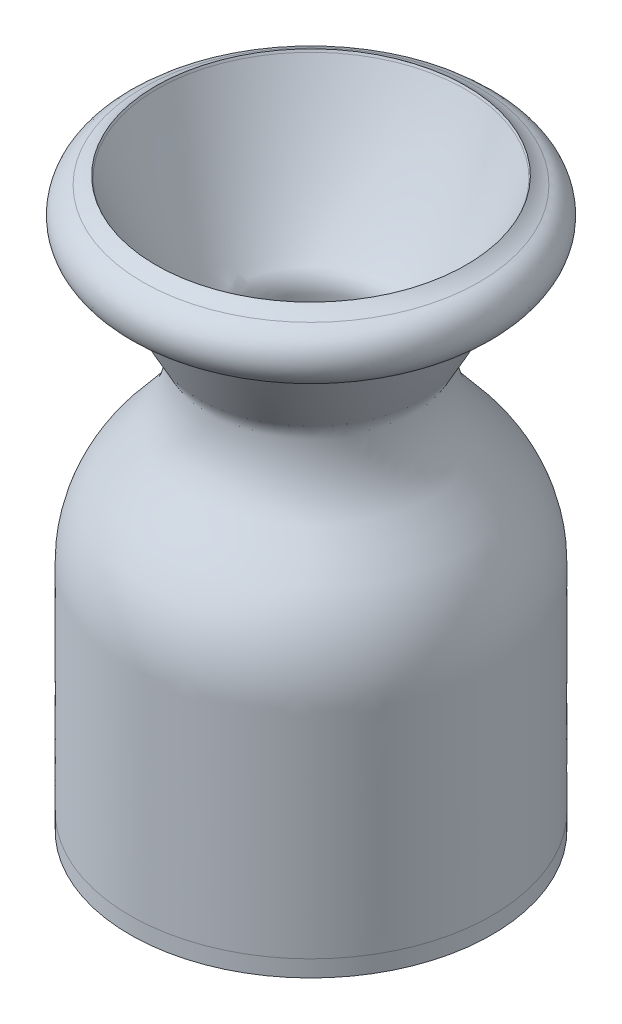
SolidWorks part; units mm, degrees
ref_plane "Front Plane" through (0, 0, 0) normal (0, 0, 1) x (1, 0, 0)
ref_plane "Top Plane" through (0, 0, 0) normal (0, 1, 0) x (1, 0, 0)
ref_plane "Right Plane" through (0, 0, 0) normal (1, 0, 0) x (0, 0, -1)
sketch "Sketch1" plane through (0, 0, 0) normal (0, 0, 1) x (1, 0, 0)
  line L0 (54.1296, -60.0027) -> (54.1296, -131.1227) construction
  line L1 (54.5811, -60.0027) -> (54.5811, -131.1227) construction
  line L2 (58.9173, -60.0026) -> (58.9173, -131.1226) construction
  line L3 (59.8203, -60.0026) -> (59.8203, -131.1226) construction
  line L4 (50.954, 50.072) -> (56.4399, 47.7573) construction
  line L5 (56.0903, 46.9289) -> (50.6035, 49.244) construction
  line L6 (53.0485, 41.5986) -> (53.88, 41.2478)
  line L7 (50.954, 50.072) -> (51.274, 50.8304)
  line L8 (0, -0.1634) -> (0, -54.0654) construction
  line L9 (54.1296, -131.1227) -> (0, -131.1227)
  line L10 (54.5811, -131.1227) -> (54.5811, -132.0219)
  line L11 (54.5811, -132.0219) -> (0, -132.0219)
  line L12 (0, -132.0219) -> (0, -131.1227)
  line L13 (58.9173, -131.1226) -> (58.9173, -134.0539)
  line L14 (58.9173, -134.0539) -> (0, -134.0539)
  line L15 (0, -134.0539) -> (0, -136.5939)
  line L16 (0, -136.5939) -> (59.8203, -136.5939)
  line L17 (59.8203, -136.5939) -> (59.8203, -131.1226)
  arc A0 (56.4399, 47.7573) -> (49.7252, 31.2954) centre (52.984, 39.5666) cw construction
  arc A1 (56.0903, 46.9289) -> (50.0823, 32.1212) centre (52.984, 39.5666) cw construction
  arc A2 (51.274, 50.8304) -> (55.6079, 48.1084) centre (61.7926, 62.7665) ccw
  arc A3 (56.0903, 46.9289) -> (50.0548, 32.1319) centre (52.984, 39.5666) cw construction
  spline S0 degree 2 poles (26.9159, 6.5388) (38.935, 21.5861) (50.954, 50.072) knots 0 0 0 1 1 1 construction
  spline S1 degree 2 poles (26.9159, 6.5388) (38.935, 21.5861) (50.954, 50.072) knots 0 0 0 1 1 1 construction
  spline S2 degree 4 poles (24.236, -0.7285) (24.2351, -0.7121) (24.2333, -0.6837) (24.23, -0.6638) (24.2239, -0.525) (24.2144, -0.4418) (24.2078, -0.111) (24.2063, 0.0033) (24.2113, 0.3156) (24.2226, 0.5546) (24.2452, 0.8681) (24.2839, 1.2051) (24.3355, 1.5509) (24.3998, 1.8885) (24.4768, 2.2272) (24.5663, 2.5604) (24.6683, 2.8915) (24.7825, 3.2177) (24.9089, 3.5399) (25.0472, 3.8568) (25.1973, 4.1686) (25.3589, 4.4743) (25.532, 4.774) (25.7158, 5.0666) (25.911, 5.3529) (26.1157, 5.6305) (26.3056, 5.8683) (26.4717, 6.064) (26.6192, 6.2287) (26.7278, 6.3465) (26.9139, 6.5383) (26.9919, 6.6143) (27.2311, 6.8443) (27.2942, 6.8944) (27.3965, 6.9882) (27.4125, 6.9995) (27.4335, 7.0181) (27.4456, 7.029) knots 0 0 0 0 0 0.005244 0.010488 0.020976 0.041953 0.083403 0.103261 0.123118 0.162834 0.20255 0.242265 0.281981 0.321697 0.361412 0.401128 0.440844 0.480559 0.520275 0.55999 0.599706 0.639422 0.679137 0.718853 0.758569 0.798284 0.838 0.857858 0.877716 0.897573 0.917431 0.958464 0.979232 0.989616 0.994808 1 1 1 1 1 construction
  spline S3 degree 4 poles (24.2075, 0.0002) (24.2075, 0.0362) (24.208, 0.1104) (24.2113, 0.3156) (24.2226, 0.5546) (24.2452, 0.8681) (24.2839, 1.2051) (24.3355, 1.5509) (24.3998, 1.8885) (24.4768, 2.2272) (24.5663, 2.5604) (24.6683, 2.8915) (24.7825, 3.2177) (24.9089, 3.5399) (25.0472, 3.8568) (25.1973, 4.1686) (25.3589, 4.4743) (25.532, 4.774) (25.7158, 5.0666) (25.911, 5.3529) (26.1157, 5.6305) (26.3056, 5.8683) (26.4717, 6.064) (26.6192, 6.2287) (26.7278, 6.3465) (26.838, 6.4601) (26.8903, 6.5132) (26.9158, 6.5387) knots 0.083403 0.083403 0.083403 0.083403 0.083403 0.103261 0.123118 0.162834 0.20255 0.242265 0.281981 0.321697 0.361412 0.401128 0.440844 0.480559 0.520275 0.55999 0.599706 0.639422 0.679137 0.718853 0.758569 0.798284 0.838 0.857858 0.877716 0.897573 0.917431 0.917431 0.917431 0.917431 0.917431 construction
  spline S4 degree 4 poles (24.3194, 2.8482) (24.3123, 2.7603) (24.2989, 2.5761) (24.2743, 2.2302) (24.2495, 1.7648) (24.2306, 1.3449) (24.2176, 0.8654) (24.2106, 0.5694) (24.2072, 0.111) (24.2072, -0.1025) (24.2112, -0.6323) (24.2223, -1.0802) (24.2445, -1.7117) (24.2826, -2.3681) (24.3334, -3.0563) (24.4126, -3.8955) (24.533, -4.911) (24.6849, -5.9156) (24.868, -6.9191) (25.076, -7.9154) (25.3089, -8.9075) (25.6165, -10.0552) (26.0169, -11.3533) (26.4655, -12.6353) (26.9617, -13.8998) (27.5049, -15.1447) (28.0943, -16.3685) (28.7289, -17.5693) (29.4081, -18.7457) (30.1306, -19.8957) (30.896, -21.0182) (31.7022, -22.1107) (32.3909, -22.9742) (32.9376, -23.6218) (33.3307, -24.0699) (33.5536, -24.3197) (33.7895, -24.578) (34.007, -24.8136) (34.2635, -25.0835) (34.4585, -25.2875) (34.7713, -25.6048) (34.9202, -25.7537) (35.311, -26.1385) (35.6354, -26.4461) (36.0678, -26.8496) (36.4019, -27.1459) (36.6838, -27.3946) (36.8112, -27.5037) (36.88, -27.5629) (36.915, -27.593) knots 0 0 0 0 0 0.010488 0.020976 0.041953 0.052315 0.062678 0.07304 0.083403 0.093332 0.103261 0.123118 0.142976 0.162834 0.182692 0.20255 0.242265 0.281981 0.301839 0.321697 0.361412 0.401128 0.440844 0.480559 0.520275 0.55999 0.599706 0.639422 0.679137 0.718853 0.758569 0.798284 0.838 0.847929 0.857858 0.867787 0.877716 0.887644 0.897573 0.907502 0.917431 0.927689 0.937948 0.958464 0.979232 0.989616 0.994808 1 1 1 1 1 construction
  spline S5 degree 4 poles (24.2075, -0.0006) (24.2075, -0.0714) (24.208, -0.2121) (24.2112, -0.6323) (24.2223, -1.0802) (24.2445, -1.7117) (24.2826, -2.3681) (24.3334, -3.0563) (24.4126, -3.8955) (24.533, -4.911) (24.6849, -5.9156) (24.868, -6.9191) (25.076, -7.9154) (25.3089, -8.9075) (25.6165, -10.0552) (26.0169, -11.3533) (26.4655, -12.6353) (26.9617, -13.8998) (27.5049, -15.1447) (28.0943, -16.3685) (28.7289, -17.5693) (29.4081, -18.7457) (30.1306, -19.8957) (30.896, -21.0182) (31.7022, -22.1107) (32.3909, -22.9742) (32.9376, -23.6218) (33.3307, -24.0699) (33.5536, -24.3197) (33.7895, -24.578) (34.007, -24.8136) (34.2635, -25.0835) (34.4585, -25.2875) (34.6911, -25.5235) (34.7923, -25.6254) (34.8423, -25.6755) knots 0.083403 0.083403 0.083403 0.083403 0.083403 0.093332 0.103261 0.123118 0.142976 0.162834 0.182692 0.20255 0.242265 0.281981 0.301839 0.321697 0.361412 0.401128 0.440844 0.480559 0.520275 0.55999 0.599706 0.639422 0.679137 0.718853 0.758569 0.798284 0.838 0.847929 0.857858 0.867787 0.877716 0.887644 0.897573 0.907502 0.917431 0.917431 0.917431 0.917431 0.917431 construction
  spline S6 degree 1 poles (34.8453, -25.6785) (43.4917, -34.3248) knots 0 0 1 1 construction
  spline S7 degree 1 poles (34.8453, -25.6785) (43.4917, -34.3248) knots 0 0 1 1 construction
  spline S8 degree 4 poles (54.02, -62.8242) (54.0234, -62.7782) (54.0302, -62.6878) (54.0431, -62.5201) (54.0666, -62.1459) (54.0933, -61.6983) (54.1138, -61.1101) (54.1257, -60.6596) (54.1299, -60.1154) (54.1299, -59.8991) (54.1259, -59.3646) (54.1166, -59.0125) (54.1021, -58.5446) (54.0822, -58.1432) (54.0632, -57.7946) (54.0243, -57.2061) (53.953, -56.3573) (53.8294, -55.2628) (53.6522, -54.0861) (53.4691, -53.0849) (53.2957, -52.2535) (53.1446, -51.5917) (52.9403, -50.7678) (52.6705, -49.7856) (52.3202, -48.6498) (51.8715, -47.3677) (51.3753, -46.1033) (50.832, -44.8583) (50.2427, -43.6346) (49.608, -42.4336) (48.9289, -41.2574) (48.206, -40.107) (47.4412, -38.9851) (46.7348, -38.0282) (46.1057, -37.2289) (45.5625, -36.5736) (45.1229, -36.0622) (44.7207, -35.6129) (44.3859, -35.2489) (44.077, -34.9232) (43.8762, -34.7135) (43.5661, -34.3988) (43.416, -34.2487) (43.026, -33.8647) (42.7009, -33.5565) (42.269, -33.1536) (41.9346, -32.8569) (41.6529, -32.6084) (41.5254, -32.4992) (41.4567, -32.44) (41.4217, -32.4099) knots 0 0 0 0 0 0.005196 0.010393 0.020785 0.041571 0.062104 0.072371 0.082638 0.092575 0.102512 0.122387 0.132324 0.142261 0.152198 0.162135 0.201884 0.241633 0.281382 0.301256 0.32113 0.341005 0.360879 0.400628 0.440377 0.480126 0.519874 0.559623 0.599372 0.639121 0.67887 0.718618 0.758367 0.798116 0.81799 0.837865 0.857739 0.877613 0.887551 0.897488 0.907425 0.917362 0.927629 0.937896 0.958429 0.979215 0.989607 0.994804 1 1 1 1 1 construction
  spline S9 degree 4 poles (54.1296, -60.0027) (54.1296, -59.9319) (54.1291, -59.7894) (54.1259, -59.3646) (54.1166, -59.0125) (54.1021, -58.5446) (54.0822, -58.1432) (54.0632, -57.7946) (54.0243, -57.2061) (53.953, -56.3573) (53.8294, -55.2628) (53.6522, -54.0861) (53.4691, -53.0849) (53.2957, -52.2535) (53.1446, -51.5917) (52.9403, -50.7678) (52.6705, -49.7856) (52.3202, -48.6498) (51.8715, -47.3677) (51.3753, -46.1033) (50.832, -44.8583) (50.2427, -43.6346) (49.608, -42.4336) (48.9289, -41.2574) (48.206, -40.107) (47.4412, -38.9851) (46.7348, -38.0282) (46.1057, -37.2289) (45.5625, -36.5736) (45.1229, -36.0622) (44.7207, -35.6129) (44.3859, -35.2489) (44.077, -34.9232) (43.8762, -34.7135) (43.6455, -34.4794) (43.5445, -34.3776) (43.4944, -34.3275) knots 0.082638 0.082638 0.082638 0.082638 0.082638 0.092575 0.102512 0.122387 0.132324 0.142261 0.152198 0.162135 0.201884 0.241633 0.281382 0.301256 0.32113 0.341005 0.360879 0.400628 0.440377 0.480126 0.519874 0.559623 0.599372 0.639121 0.67887 0.718618 0.758367 0.798116 0.81799 0.837865 0.857739 0.877613 0.887551 0.897488 0.907425 0.917362 0.917362 0.917362 0.917362 0.917362 construction
  spline S10 degree 4 poles (24.8536, 3.3681) (24.9061, 3.4281) (25.0099, 3.547) (25.2062, 3.7719) (25.5239, 4.1426) (25.8477, 4.5222) (26.2859, 5.0484) (26.6268, 5.4602) (27.1711, 6.1336) (27.4577, 6.4932) (28.1026, 7.3122) (28.503, 7.8373) (29.0623, 8.5727) (29.5173, 9.1883) (30.0267, 9.8826) (30.495, 10.5357) (30.9795, 11.2189) (31.4472, 11.8906) (32.0332, 12.7436) (32.7231, 13.7686) (33.5173, 14.9762) (34.4065, 16.3654) (35.2802, 17.7661) (36.1378, 19.1755) (37.0434, 20.6993) (38.1387, 22.5891) (39.4112, 24.8546) (40.8445, 27.4996) (42.1808, 30.0626) (43.2975, 32.2679) (44.3975, 34.4919) (45.2919, 36.3383) (46.1826, 38.2197) (47.2137, 40.4375) (48.0895, 42.3647) (48.8951, 44.1631) (49.7765, 46.1768) (50.3403, 47.4735) (51.2686, 49.652) (51.641, 50.5383) (52.5159, 52.6334) (52.7792, 53.2856) (53.1126, 54.0939) (53.1825, 54.2695) (53.2488, 54.4316) (53.2859, 54.5223) knots 0 0 0 0 0 0.005289 0.010577 0.021154 0.031564 0.041975 0.053053 0.064131 0.078173 0.092214 0.106255 0.120297 0.134338 0.14838 0.162421 0.176463 0.190504 0.204546 0.232628 0.260711 0.288794 0.316877 0.34496 0.373043 0.409429 0.465595 0.521761 0.577926 0.606009 0.634092 0.690258 0.718341 0.746424 0.802589 0.830672 0.858755 0.886838 0.914921 0.957461 0.97873 0.989365 0.994683 1 1 1 1 1 construction
  spline S11 degree 4 poles (27.2713, 6.2602) (27.3808, 6.3973) (27.592, 6.6638) (28.1026, 7.3122) (28.503, 7.8373) (29.0623, 8.5727) (29.5173, 9.1883) (30.0267, 9.8826) (30.495, 10.5357) (30.9795, 11.2189) (31.4472, 11.8906) (32.0332, 12.7436) (32.7231, 13.7686) (33.5173, 14.9762) (34.4065, 16.3654) (35.2802, 17.7661) (36.1378, 19.1755) (37.0434, 20.6993) (38.1387, 22.5891) (39.4112, 24.8546) (40.8445, 27.4996) (42.1808, 30.0626) (43.2975, 32.2679) (44.3975, 34.4919) (45.2919, 36.3383) (46.1826, 38.2197) (47.2137, 40.4375) (48.0895, 42.3647) (48.8951, 44.1631) (49.7765, 46.1768) (50.3403, 47.4735) (50.9571, 48.9211) (51.2336, 49.5731) (51.37, 49.8965) knots 0.064131 0.064131 0.064131 0.064131 0.064131 0.078173 0.092214 0.106255 0.120297 0.134338 0.14838 0.162421 0.176463 0.190504 0.204546 0.232628 0.260711 0.288794 0.316877 0.34496 0.373043 0.409429 0.465595 0.521761 0.577926 0.606009 0.634092 0.690258 0.718341 0.746424 0.802589 0.830672 0.858755 0.886838 0.914921 0.914921 0.914921 0.914921 0.914921 construction
  spline S12 degree 4 poles (24.6861, -0.6929) (24.6852, -0.6774) (24.6836, -0.6503) (24.6804, -0.6314) (24.6746, -0.4993) (24.6656, -0.4202) (24.6593, -0.1055) (24.6579, 0.0031) (24.6626, 0.3002) (24.6734, 0.5275) (24.6949, 0.8257) (24.7317, 1.1462) (24.7808, 1.4752) (24.8419, 1.7963) (24.9151, 2.1184) (25.0003, 2.4354) (25.0973, 2.7503) (25.206, 3.0606) (25.3262, 3.367) (25.4577, 3.6685) (25.6005, 3.965) (25.7542, 4.2558) (25.9188, 4.5409) (26.0936, 4.8193) (26.2794, 5.0915) (26.4741, 5.3556) (26.6547, 5.5818) (26.8126, 5.768) (26.9529, 5.9245) (27.0563, 6.0366) (27.2332, 6.2191) (27.3075, 6.2913) (27.535, 6.5101) (27.595, 6.5578) (27.6923, 6.647) (27.7075, 6.6577) (27.7275, 6.6755) (27.739, 6.6858) knots 0 0 0 0 0 0.005244 0.010488 0.020976 0.041953 0.083403 0.103261 0.123118 0.162834 0.20255 0.242265 0.281981 0.321697 0.361412 0.401128 0.440844 0.480559 0.520275 0.55999 0.599706 0.639422 0.679137 0.718853 0.758569 0.798284 0.838 0.857858 0.877716 0.897573 0.917431 0.958464 0.979232 0.989616 0.994808 1 1 1 1 1 construction
  spline S13 degree 4 poles (24.659, 0.0002) (24.659, 0.0344) (24.6595, 0.105) (24.6626, 0.3002) (24.6734, 0.5275) (24.6949, 0.8257) (24.7317, 1.1462) (24.7808, 1.4752) (24.8419, 1.7963) (24.9151, 2.1184) (25.0003, 2.4354) (25.0973, 2.7503) (25.206, 3.0606) (25.3262, 3.367) (25.4577, 3.6685) (25.6005, 3.965) (25.7542, 4.2558) (25.9188, 4.5409) (26.0936, 4.8193) (26.2794, 5.0915) (26.4741, 5.3556) (26.6547, 5.5818) (26.8126, 5.768) (26.9529, 5.9245) (27.0563, 6.0366) (27.1611, 6.1447) (27.2109, 6.1952) (27.2351, 6.2194) knots 0.083403 0.083403 0.083403 0.083403 0.083403 0.103261 0.123118 0.162834 0.20255 0.242265 0.281981 0.321697 0.361412 0.401128 0.440844 0.480559 0.520275 0.55999 0.599706 0.639422 0.679137 0.718853 0.758569 0.798284 0.838 0.857858 0.877716 0.897573 0.917431 0.917431 0.917431 0.917431 0.917431 construction
  spline S14 degree 4 poles (24.7695, 2.8132) (24.766, 2.7683) (24.7592, 2.6792) (24.7462, 2.5068) (24.7225, 2.1445) (24.6956, 1.6777) (24.675, 1.1213) (24.663, 0.6371) (24.6579, 0.0244) (24.6592, -0.2104) (24.6658, -0.8243) (24.6799, -1.2196) (24.7003, -1.7854) (24.7332, -2.3313) (24.7833, -3.0216) (24.8616, -3.8449) (24.9805, -4.8515) (25.1304, -5.841) (25.3113, -6.8335) (25.5168, -7.8166) (25.7084, -8.6338) (25.9203, -9.4442) (26.1988, -10.4111) (26.5013, -11.3703) (26.8889, -12.4783) (27.379, -13.7269) (27.9154, -14.9564) (28.4974, -16.165) (29.1242, -17.3509) (29.7949, -18.5126) (30.5085, -19.6483) (31.2643, -20.7568) (32.0605, -21.8358) (32.7406, -22.6885) (33.2805, -23.3281) (33.6688, -23.7706) (33.8889, -24.0173) (34.1218, -24.2724) (34.3367, -24.505) (34.59, -24.7716) (34.7825, -24.973) (35.0914, -25.2864) (35.2385, -25.4335) (35.6245, -25.8135) (35.9448, -26.1173) (36.3719, -26.5157) (36.7018, -26.8084) (36.9802, -27.0539) (37.106, -27.1617) (37.1739, -27.2201) (37.2085, -27.2499) knots 0 0 0 0 0 0.005244 0.010488 0.020976 0.041953 0.062678 0.07304 0.083403 0.103261 0.11319 0.123118 0.142976 0.162834 0.182692 0.20255 0.242265 0.281981 0.301839 0.321697 0.361412 0.38127 0.401128 0.440844 0.480559 0.520275 0.55999 0.599706 0.639422 0.679137 0.718853 0.758569 0.798284 0.838 0.847929 0.857858 0.867787 0.877716 0.887644 0.897573 0.907502 0.917431 0.927689 0.937948 0.958464 0.979232 0.989616 0.994808 1 1 1 1 1 construction
  spline S15 degree 4 poles (24.659, -0.0006) (24.659, -0.1404) (24.6606, -0.3374) (24.6658, -0.8243) (24.6799, -1.2196) (24.7003, -1.7854) (24.7332, -2.3313) (24.7833, -3.0216) (24.8616, -3.8449) (24.9805, -4.8515) (25.1304, -5.841) (25.3113, -6.8335) (25.5168, -7.8166) (25.7084, -8.6338) (25.9203, -9.4442) (26.1988, -10.4111) (26.5013, -11.3703) (26.8889, -12.4783) (27.379, -13.7269) (27.9154, -14.9564) (28.4974, -16.165) (29.1242, -17.3509) (29.7949, -18.5126) (30.5085, -19.6483) (31.2643, -20.7568) (32.0605, -21.8358) (32.7406, -22.6885) (33.2805, -23.3281) (33.6688, -23.7706) (33.8889, -24.0173) (34.1218, -24.2724) (34.3367, -24.505) (34.59, -24.7716) (34.7825, -24.973) (35.0123, -25.2061) (35.1122, -25.3068) (35.1616, -25.3562) knots 0.083403 0.083403 0.083403 0.083403 0.083403 0.103261 0.11319 0.123118 0.142976 0.162834 0.182692 0.20255 0.242265 0.281981 0.301839 0.321697 0.361412 0.38127 0.401128 0.440844 0.480559 0.520275 0.55999 0.599706 0.639422 0.679137 0.718853 0.758569 0.798284 0.838 0.847929 0.857858 0.867787 0.877716 0.887644 0.897573 0.907502 0.917431 0.917431 0.917431 0.917431 0.917431 construction
  spline S16 degree 1 poles (35.1646, -25.3592) (43.811, -34.0056) knots 0 0 1 1 construction
  spline S17 degree 1 poles (35.1646, -25.3592) (43.811, -34.0056) knots 0 0 1 1 construction
  spline S18 degree 4 poles (54.4701, -62.8587) (54.4736, -62.8131) (54.4804, -62.7225) (54.4935, -62.548) (54.5173, -62.1792) (54.5443, -61.7074) (54.5651, -61.1396) (54.5771, -60.6516) (54.5822, -60.0252) (54.5809, -59.7895) (54.5741, -59.1418) (54.5621, -58.8473) (54.5492, -58.4263) (54.5332, -58.1301) (54.5139, -57.7618) (54.4858, -57.3455) (54.4456, -56.8249) (54.3734, -56.0584) (54.2515, -55.032) (54.0722, -53.8437) (53.8485, -52.6604) (53.6252, -51.654) (53.377, -50.6529) (53.1039, -49.6586) (52.7492, -48.5086) (52.295, -47.2107) (51.7925, -45.9305) (51.2426, -44.6701) (50.6458, -43.431) (50.0034, -42.2153) (49.3155, -41.0241) (48.5843, -39.86) (47.8089, -38.7231) (46.9934, -37.6178) (46.2413, -36.6751) (45.5765, -35.8923) (45.0562, -35.3106) (44.7161, -34.941) (44.4029, -34.6108) (44.2018, -34.4006) (43.8844, -34.0786) (43.7372, -33.9314) (43.4059, -33.6049) (43.1937, -33.4025) (42.8431, -33.0701) (42.5335, -32.787) (42.1853, -32.4736) (41.9233, -32.2462) (41.7831, -32.1249) (41.7159, -32.0676) knots 0 0 0 0 0 0.005196 0.010393 0.020785 0.041571 0.062104 0.072371 0.082638 0.102512 0.112449 0.122387 0.132324 0.142261 0.152198 0.162135 0.18201 0.201884 0.241633 0.281382 0.32113 0.341005 0.360879 0.400628 0.440377 0.480126 0.519874 0.559623 0.599372 0.639121 0.67887 0.718618 0.758367 0.798116 0.837865 0.857739 0.877613 0.887551 0.897488 0.907425 0.917362 0.927629 0.937896 0.948162 0.958429 0.979215 0.989607 1 1 1 1 1 construction
  spline S19 degree 4 poles (54.5811, -60.0027) (54.5811, -59.8592) (54.5795, -59.6565) (54.5741, -59.1418) (54.5621, -58.8473) (54.5492, -58.4263) (54.5332, -58.1301) (54.5139, -57.7618) (54.4858, -57.3455) (54.4456, -56.8249) (54.3734, -56.0584) (54.2515, -55.032) (54.0722, -53.8437) (53.8485, -52.6604) (53.6252, -51.654) (53.377, -50.6529) (53.1039, -49.6586) (52.7492, -48.5086) (52.295, -47.2107) (51.7925, -45.9305) (51.2426, -44.6701) (50.6458, -43.431) (50.0034, -42.2153) (49.3155, -41.0241) (48.5843, -39.86) (47.8089, -38.7231) (46.9934, -37.6178) (46.2413, -36.6751) (45.5765, -35.8923) (45.0562, -35.3106) (44.7161, -34.941) (44.4029, -34.6108) (44.2018, -34.4006) (43.9657, -34.1611) (43.8643, -34.0589) (43.8136, -34.0082) knots 0.082638 0.082638 0.082638 0.082638 0.082638 0.102512 0.112449 0.122387 0.132324 0.142261 0.152198 0.162135 0.18201 0.201884 0.241633 0.281382 0.32113 0.341005 0.360879 0.400628 0.440377 0.480126 0.519874 0.559623 0.599372 0.639121 0.67887 0.718618 0.758367 0.798116 0.837865 0.857739 0.877613 0.887551 0.897488 0.907425 0.917362 0.917362 0.917362 0.917362 0.917362 construction
  spline S20 degree 4 poles (31.45, -2.4229) (31.519, -2.3094) (31.6746, -2.0521) (31.9025, -1.6783) (32.3898, -0.8647) (32.7396, -0.2828) (33.4267, 0.8822) (33.7367, 1.4111) (34.4377, 2.6162) (35.0294, 3.6491) (35.8409, 5.0795) (36.6785, 6.5866) (37.5473, 8.1721) (38.3803, 9.7216) (39.2171, 11.3021) (40.0342, 12.8731) (40.8461, 14.4586) (41.6444, 16.0441) (42.4345, 17.6376) (43.2136, 19.2345) (43.9835, 20.8364) (44.779, 22.5174) (45.7513, 24.6038) (46.8937, 27.1065) (48.0098, 29.6106) (49.0779, 32.0632) (49.9474, 34.0931) (50.6482, 35.7534) (51.3166, 37.3516) (52.0204, 39.0635) (52.811, 40.9981) (53.7223, 43.2808) (54.403, 44.9966) (55.4937, 47.8078) (55.8637, 48.773) (56.7014, 50.9707) (56.9634, 51.677) (57.2781, 52.5114) (57.3487, 52.7038) (57.4117, 52.8721) (57.4468, 52.9657) knots 0 0 0 0 0 0.008652 0.017304 0.034608 0.05166 0.068712 0.083217 0.097722 0.126732 0.155742 0.184753 0.213763 0.242773 0.271783 0.300794 0.329804 0.358814 0.387824 0.416835 0.445845 0.474855 0.509194 0.567214 0.625235 0.654245 0.683255 0.712266 0.741276 0.770286 0.799296 0.857317 0.886327 0.915337 0.957669 0.978834 0.989417 0.994709 1 1 1 1 1 construction
  spline S21 degree 4 poles (33.6109, 1.197) (33.7059, 1.3593) (33.8959, 1.6848) (34.4377, 2.6162) (35.0294, 3.6491) (35.8409, 5.0795) (36.6785, 6.5866) (37.5473, 8.1721) (38.3803, 9.7216) (39.2171, 11.3021) (40.0342, 12.8731) (40.8461, 14.4586) (41.6444, 16.0441) (42.4345, 17.6376) (43.2136, 19.2345) (43.9835, 20.8364) (44.779, 22.5174) (45.7513, 24.6038) (46.8937, 27.1065) (48.0098, 29.6106) (49.0779, 32.0632) (49.9474, 34.0931) (50.6482, 35.7534) (51.3166, 37.3516) (52.0204, 39.0635) (52.811, 40.9981) (53.7223, 43.2808) (54.403, 44.9966) (55.2022, 47.0564) (55.4729, 47.7573) (55.6079, 48.1084) knots 0.068712 0.068712 0.068712 0.068712 0.068712 0.083217 0.097722 0.126732 0.155742 0.184753 0.213763 0.242773 0.271783 0.300794 0.329804 0.358814 0.387824 0.416835 0.445845 0.474855 0.509194 0.567214 0.625235 0.654245 0.683255 0.712266 0.741276 0.770286 0.799296 0.857317 0.886327 0.915337 0.915337 0.915337 0.915337 0.915337 construction
  spline S22 degree 4 poles (32.1289, -3.0183) (32.1987, -2.904) (32.3565, -2.644) (32.5868, -2.2678) (33.0809, -1.4458) (33.4341, -0.8605) (34.1295, 0.3147) (34.4416, 0.8457) (35.1462, 2.0537) (35.7404, 3.0879) (36.5546, 4.5194) (37.3953, 6.0282) (38.2669, 7.6154) (39.1027, 9.1666) (39.9422, 10.7489) (40.762, 12.3218) (41.5764, 13.9092) (42.3773, 15.4966) (43.1698, 17.0921) (43.9513, 18.6911) (44.7236, 20.295) (45.539, 22.0151) (46.531, 24.1414) (47.508, 26.2803) (48.4656, 28.4176) (49.3645, 30.4629) (50.0679, 32.0824) (50.954, 34.1544) (51.7991, 36.158) (52.678, 38.2862) (53.6434, 40.6501) (54.5473, 42.9129) (55.2345, 44.6449) (56.326, 47.4576) (56.6974, 48.4263) (57.539, 50.6337) (57.802, 51.3426) (58.1184, 52.1813) (58.1893, 52.3745) (58.2526, 52.5437) (58.2879, 52.6377) knots 0 0 0 0 0 0.008692 0.017384 0.034768 0.051899 0.069029 0.083484 0.097938 0.126848 0.155757 0.184666 0.213576 0.242485 0.271394 0.300303 0.329213 0.358122 0.387031 0.415941 0.44485 0.473759 0.510636 0.568454 0.597364 0.626273 0.655182 0.684092 0.74191 0.77082 0.799729 0.857548 0.886457 0.915366 0.957683 0.978842 0.989421 0.99471 1 1 1 1 1 construction
  spline S23 degree 4 poles (34.3165, 0.6334) (34.4118, 0.7958) (34.6027, 1.1218) (35.1462, 2.0537) (35.7404, 3.0879) (36.5546, 4.5194) (37.3953, 6.0282) (38.2669, 7.6154) (39.1027, 9.1666) (39.9422, 10.7489) (40.762, 12.3218) (41.5764, 13.9092) (42.3773, 15.4966) (43.1698, 17.0921) (43.9513, 18.6911) (44.7236, 20.295) (45.539, 22.0151) (46.531, 24.1414) (47.508, 26.2803) (48.4656, 28.4176) (49.3645, 30.4629) (50.0679, 32.0824) (50.954, 34.1544) (51.7991, 36.158) (52.678, 38.2862) (53.6434, 40.6501) (54.5473, 42.9129) (55.2345, 44.6449) (56.0336, 46.7041) (56.3047, 47.4058) (56.4399, 47.7573) knots 0.069029 0.069029 0.069029 0.069029 0.069029 0.083484 0.097938 0.126848 0.155757 0.184666 0.213576 0.242485 0.271394 0.300303 0.329213 0.358122 0.387031 0.415941 0.44485 0.473759 0.510636 0.568454 0.597364 0.626273 0.655182 0.684092 0.74191 0.77082 0.799729 0.857548 0.886457 0.915366 0.915366 0.915366 0.915366 0.915366 construction
  spline S24 degree 4 poles (33.2855, 2.1456) (33.2818, 2.0729) (33.2748, 1.9331) (33.262, 1.7038) (33.2465, 1.2196) (33.2337, 0.8913) (33.2269, 0.1904) (33.2264, -0.0817) (33.2306, -0.6155) (33.2383, -0.9639) (33.2529, -1.4709) (33.2781, -2.044) (33.3188, -2.7339) (33.3732, -3.4097) (33.4296, -3.9951) (33.494, -4.5757) (33.5662, -5.1575) (33.6622, -5.8332) (33.788, -6.604) (33.93, -7.3714) (34.0884, -8.1359) (34.3072, -9.0869) (34.5706, -10.0953) (34.8668, -11.0947) (35.1962, -12.0834) (35.485, -12.8798) (35.7684, -13.6069) (36.0698, -14.3276) (36.3879, -15.0395) (36.725, -15.7453) (37.0774, -16.4392) (37.4513, -17.1291) (37.8362, -17.8006) (38.2495, -18.4761) (38.6612, -19.1162) (39.0674, -19.7065) (39.375, -20.1384) (39.7554, -20.6468) (39.929, -20.872) (40.3707, -21.4329) (40.5905, -21.6896) (40.9154, -22.077) (41.0706, -22.249) (41.1695, -22.3614) (41.2208, -22.4195) knots 0 0 0 0 0 0.010123 0.020245 0.040491 0.060736 0.080982 0.095722 0.110462 0.125203 0.139943 0.169423 0.198904 0.228384 0.243124 0.257865 0.287345 0.316826 0.346306 0.375787 0.405267 0.434748 0.493709 0.533207 0.562687 0.592168 0.621648 0.651129 0.680609 0.71009 0.73957 0.76905 0.798531 0.828011 0.857492 0.886972 0.901713 0.916453 0.937214 0.957975 0.978987 0.989494 1 1 1 1 1 construction
  spline S25 degree 4 poles (33.227, -0.0005) (33.227, -0.082) (33.2277, -0.2494) (33.2306, -0.6155) (33.2383, -0.9639) (33.2529, -1.4709) (33.2781, -2.044) (33.3188, -2.7339) (33.3732, -3.4097) (33.4296, -3.9951) (33.494, -4.5757) (33.5662, -5.1575) (33.6622, -5.8332) (33.788, -6.604) (33.93, -7.3714) (34.0884, -8.1359) (34.3072, -9.0869) (34.5706, -10.0953) (34.8668, -11.0947) (35.1962, -12.0834) (35.485, -12.8798) (35.7684, -13.6069) (36.0698, -14.3276) (36.3879, -15.0395) (36.725, -15.7453) (37.0774, -16.4392) (37.4513, -17.1291) (37.8362, -17.8006) (38.2495, -18.4761) (38.6612, -19.1162) (39.0674, -19.7065) (39.375, -20.1384) (39.6564, -20.5144) (39.7568, -20.6469) (39.8063, -20.7116) knots 0.080982 0.080982 0.080982 0.080982 0.080982 0.095722 0.110462 0.125203 0.139943 0.169423 0.198904 0.228384 0.243124 0.257865 0.287345 0.316826 0.346306 0.375787 0.405267 0.434748 0.493709 0.533207 0.562687 0.592168 0.621648 0.651129 0.680609 0.71009 0.73957 0.76905 0.798531 0.828011 0.857492 0.886972 0.901713 0.916453 0.916453 0.916453 0.916453 0.916453 construction
  spline S26 degree 4 poles (39.047, -19.7451) (39.0634, -19.766) (39.0923, -19.8029) (39.117, -19.8347) (39.2548, -20.0103) (39.3546, -20.1383) (39.7149, -20.5959) (39.85, -20.7672) (40.2386, -21.258) (40.4549, -21.5297) (40.7513, -21.9019) (41.0008, -22.2134) (41.2793, -22.5608) (41.5412, -22.8859) (41.8137, -23.2236) (42.0811, -23.5537) (42.3515, -23.8867) (42.6221, -24.219) (42.8912, -24.5486) (43.2138, -24.9424) (43.5953, -25.407) (44.0644, -25.9752) (44.5716, -26.5877) (45.1488, -27.2799) (45.6516, -27.8817) (46.2775, -28.6253) (46.7056, -29.1335) (47.4099, -29.9634) (47.669, -30.2681) (48.0173, -30.6763) (48.262, -30.963) (48.3158, -31.0256) (48.3923, -31.1152) (48.4109, -31.1368) knots 0 0 0 0 0 0.00524 0.010481 0.020962 0.041923 0.083345 0.112371 0.141398 0.170425 0.199451 0.228478 0.257505 0.286531 0.315558 0.344585 0.373611 0.402638 0.431664 0.460691 0.51042 0.568474 0.626527 0.68458 0.742633 0.800687 0.85874 0.916793 0.958397 0.979198 0.989599 1 1 1 1 1 construction
  spline S27 degree 4 poles (39.8089, -20.7149) (39.8642, -20.7849) (39.9753, -20.9254) (40.2386, -21.258) (40.4549, -21.5297) (40.7513, -21.9019) (41.0008, -22.2134) (41.2793, -22.5608) (41.5412, -22.8859) (41.8137, -23.2236) (42.0811, -23.5537) (42.3515, -23.8867) (42.6221, -24.219) (42.8912, -24.5486) (43.2138, -24.9424) (43.5953, -25.407) (44.0644, -25.9752) (44.5716, -26.5877) (45.1488, -27.2799) (45.6516, -27.8817) (46.2775, -28.6253) (46.7056, -29.1335) (47.2741, -29.8034) (47.4981, -30.0671) (47.6137, -30.2029) knots 0.083345 0.083345 0.083345 0.083345 0.083345 0.112371 0.141398 0.170425 0.199451 0.228478 0.257505 0.286531 0.315558 0.344585 0.373611 0.402638 0.431664 0.460691 0.51042 0.568474 0.626527 0.68458 0.742633 0.800687 0.85874 0.916793 0.916793 0.916793 0.916793 0.916793 construction
  spline S28 degree 4 poles (58.7994, -63.2285) (58.8032, -63.1768) (58.8104, -63.0744) (58.8243, -62.8777) (58.8496, -62.46) (58.8783, -61.9291) (58.9003, -61.2849) (58.9131, -60.7371) (58.9181, -60.0772) (58.9173, -59.7728) (58.9096, -59.0054) (58.893, -58.5384) (58.868, -57.8486) (58.8346, -57.2928) (58.793, -56.6582) (58.7431, -56.0698) (58.6703, -55.3054) (58.5837, -54.5584) (58.4834, -53.803) (58.3465, -52.9051) (58.1933, -52.007) (57.9908, -50.9654) (57.7268, -49.7805) (57.4308, -48.6039) (57.1029, -47.4353) (56.7435, -46.2764) (56.3529, -45.1273) (55.9317, -43.9895) (55.4798, -42.8629) (54.9985, -41.7495) (54.3806, -40.4192) (53.72, -39.1127) (53.0123, -37.825) (52.2682, -36.5681) (51.6167, -35.5338) (50.9555, -34.5355) (50.24, -33.5211) (49.55, -32.5829) (48.8435, -31.6832) (48.3544, -31.0759) (47.7703, -30.3847) (47.5634, -30.1435) (47.2088, -29.7375) (46.9445, -29.4408) (46.6047, -29.0652) (46.2574, -28.6892) (45.9099, -28.3213) (45.6264, -28.027) (45.4849, -27.8818) (45.4136, -27.809) knots 0 0 0 0 0 0.005199 0.010399 0.020797 0.041595 0.06214 0.072413 0.082686 0.098226 0.113766 0.129305 0.144845 0.160385 0.175925 0.191465 0.207005 0.238085 0.253625 0.269165 0.300244 0.331324 0.362404 0.393484 0.424564 0.455644 0.486723 0.517803 0.548883 0.579963 0.611043 0.667969 0.699049 0.730129 0.761209 0.792289 0.823368 0.854448 0.885528 0.901068 0.916608 0.927032 0.937456 0.94788 0.958304 0.979152 0.989576 1 1 1 1 1 construction
  spline S29 degree 4 poles (58.9173, -60.0026) (58.9173, -59.8761) (58.9159, -59.6343) (58.9096, -59.0054) (58.893, -58.5384) (58.868, -57.8486) (58.8346, -57.2928) (58.793, -56.6582) (58.7431, -56.0698) (58.6703, -55.3054) (58.5837, -54.5584) (58.4834, -53.803) (58.3465, -52.9051) (58.1933, -52.007) (57.9908, -50.9654) (57.7268, -49.7805) (57.4308, -48.6039) (57.1029, -47.4353) (56.7435, -46.2764) (56.3529, -45.1273) (55.9317, -43.9895) (55.4798, -42.8629) (54.9985, -41.7495) (54.3806, -40.4192) (53.72, -39.1127) (53.0123, -37.825) (52.2682, -36.5681) (51.6167, -35.5338) (50.9555, -34.5355) (50.24, -33.5211) (49.55, -32.5829) (48.8435, -31.6832) (48.3544, -31.0759) (47.8542, -30.484) (47.6987, -30.3016) (47.6161, -30.2057) knots 0.082686 0.082686 0.082686 0.082686 0.082686 0.098226 0.113766 0.129305 0.144845 0.160385 0.175925 0.191465 0.207005 0.238085 0.253625 0.269165 0.300244 0.331324 0.362404 0.393484 0.424564 0.455644 0.486723 0.517803 0.548883 0.579963 0.611043 0.667969 0.699049 0.730129 0.761209 0.792289 0.823368 0.854448 0.885528 0.901068 0.916608 0.916608 0.916608 0.916608 0.916608 construction
  spline S30 degree 4 poles (34.1857, 2.0749) (34.1822, 2.0045) (34.1756, 1.869) (34.1634, 1.647) (34.1486, 1.1808) (34.1364, 0.8589) (34.13, 0.1878) (34.1294, -0.0839) (34.1344, -0.6965) (34.1474, -1.2081) (34.1733, -1.9038) (34.2178, -2.6379) (34.2772, -3.405) (34.3424, -4.055) (34.4078, -4.6236) (34.4686, -5.0896) (34.5211, -5.4655) (34.5915, -5.9322) (34.6838, -6.4923) (34.8368, -7.3291) (35.0331, -8.2542) (35.2562, -9.173) (35.5222, -10.1426) (35.7578, -10.9242) (36.0131, -11.6994) (36.2887, -12.468) (36.5605, -13.1735) (36.8498, -13.8729) (37.1553, -14.564) (37.4793, -15.249) (37.8179, -15.9227) (38.1775, -16.5926) (38.5477, -17.2448) (38.9455, -17.901) (39.3418, -18.5226) (39.733, -19.0964) (40.0292, -19.5159) (40.3958, -20.01) (40.5629, -20.2288) (40.9885, -20.7738) (41.1998, -21.0227) (41.5134, -21.3998) (41.6623, -21.5662) (41.7581, -21.6759) (41.8074, -21.7324) knots 0 0 0 0 0 0.010111 0.020223 0.040446 0.060669 0.080892 0.095645 0.110399 0.139906 0.169413 0.198921 0.228428 0.257935 0.272689 0.287442 0.302196 0.316949 0.346457 0.375964 0.434978 0.464486 0.493993 0.532851 0.562358 0.591865 0.621372 0.65088 0.680387 0.709894 0.739401 0.768909 0.798416 0.827923 0.85743 0.886937 0.901691 0.916445 0.937208 0.957971 0.978985 0.989493 1 1 1 1 1 construction
  spline S31 degree 4 poles (34.1301, -0.0005) (34.1301, -0.0795) (34.1307, -0.2402) (34.1344, -0.6965) (34.1474, -1.2081) (34.1733, -1.9038) (34.2178, -2.6379) (34.2772, -3.405) (34.3424, -4.055) (34.4078, -4.6236) (34.4686, -5.0896) (34.5211, -5.4655) (34.5915, -5.9322) (34.6838, -6.4923) (34.8368, -7.3291) (35.0331, -8.2542) (35.2562, -9.173) (35.5222, -10.1426) (35.7578, -10.9242) (36.0131, -11.6994) (36.2887, -12.468) (36.5605, -13.1735) (36.8498, -13.8729) (37.1553, -14.564) (37.4793, -15.249) (37.8179, -15.9227) (38.1775, -16.5926) (38.5477, -17.2448) (38.9455, -17.901) (39.3418, -18.5226) (39.733, -19.0964) (40.0292, -19.5159) (40.3004, -19.8814) (40.3971, -20.0102) (40.4449, -20.0731) knots 0.080892 0.080892 0.080892 0.080892 0.080892 0.095645 0.110399 0.139906 0.169413 0.198921 0.228428 0.257935 0.272689 0.287442 0.302196 0.316949 0.346457 0.375964 0.434978 0.464486 0.493993 0.532851 0.562358 0.591865 0.621372 0.65088 0.680387 0.709894 0.739401 0.768909 0.798416 0.827923 0.85743 0.886937 0.901691 0.916445 0.916445 0.916445 0.916445 0.916445 construction
  spline S32 degree 4 poles (39.6856, -19.1066) (39.7019, -19.1274) (39.7308, -19.1644) (39.7555, -19.1962) (39.8933, -19.3718) (39.9931, -19.4998) (40.3534, -19.9574) (40.4885, -20.1286) (40.8771, -20.6195) (41.0934, -20.8912) (41.3899, -21.2634) (41.6393, -21.5749) (41.9179, -21.9222) (42.1798, -22.2474) (42.4523, -22.5851) (42.7196, -22.9151) (42.99, -23.2482) (43.2606, -23.5804) (43.5297, -23.91) (43.8523, -24.3039) (44.2338, -24.7684) (44.7029, -25.3367) (45.2101, -25.9492) (45.7873, -26.6414) (46.2901, -27.2432) (46.916, -27.9867) (47.3441, -28.495) (48.0484, -29.3249) (48.3076, -29.6295) (48.6558, -30.0378) (48.9005, -30.3244) (48.9544, -30.3871) (49.0309, -30.4767) (49.0494, -30.4983) knots 0 0 0 0 0 0.00524 0.010481 0.020962 0.041923 0.083345 0.112371 0.141398 0.170425 0.199451 0.228478 0.257505 0.286531 0.315558 0.344585 0.373611 0.402638 0.431664 0.460691 0.51042 0.568474 0.626527 0.68458 0.742633 0.800687 0.85874 0.916793 0.958397 0.979198 0.989599 1 1 1 1 1 construction
  spline S33 degree 4 poles (40.4474, -20.0764) (40.5027, -20.1463) (40.6138, -20.2869) (40.8771, -20.6195) (41.0934, -20.8912) (41.3899, -21.2634) (41.6393, -21.5749) (41.9179, -21.9222) (42.1798, -22.2474) (42.4523, -22.5851) (42.7196, -22.9151) (42.99, -23.2482) (43.2606, -23.5804) (43.5297, -23.91) (43.8523, -24.3039) (44.2338, -24.7684) (44.7029, -25.3367) (45.2101, -25.9492) (45.7873, -26.6414) (46.2901, -27.2432) (46.916, -27.9867) (47.3441, -28.495) (47.9126, -29.1649) (48.1367, -29.4285) (48.2522, -29.5643) knots 0.083345 0.083345 0.083345 0.083345 0.083345 0.112371 0.141398 0.170425 0.199451 0.228478 0.257505 0.286531 0.315558 0.344585 0.373611 0.402638 0.431664 0.460691 0.51042 0.568474 0.626527 0.68458 0.742633 0.800687 0.85874 0.916793 0.916793 0.916793 0.916793 0.916793 construction
  spline S34 degree 4 poles (59.6997, -63.3006) (59.7035, -63.2456) (59.7109, -63.1385) (59.7251, -62.9501) (59.751, -62.4945) (59.7751, -62.1026) (59.7954, -61.4866) (59.8123, -61.0054) (59.8208, -60.2081) (59.8217, -59.882) (59.8125, -59.0016) (59.7954, -58.4949) (59.7698, -57.8089) (59.7357, -57.2295) (59.6931, -56.5879) (59.642, -55.9829) (59.5676, -55.2041) (59.479, -54.4394) (59.3763, -53.6684) (59.2363, -52.7506) (59.0795, -51.8331) (58.8723, -50.7687) (58.6022, -49.5582) (58.2993, -48.3561) (57.9638, -47.1623) (57.596, -45.9783) (57.1963, -44.8044) (56.7653, -43.642) (56.3028, -42.4912) (55.8104, -41.3539) (55.178, -39.9951) (54.5019, -38.6607) (53.7777, -37.3455) (53.0162, -36.0621) (52.3494, -35.0059) (51.6726, -33.9866) (50.9404, -32.951) (50.2341, -31.9933) (49.5109, -31.0749) (49.0104, -30.4551) (48.4125, -29.7498) (48.2007, -29.5037) (47.8377, -29.0894) (47.5671, -28.7867) (47.2193, -28.4035) (46.8638, -28.0199) (46.5081, -27.6446) (46.2179, -27.3445) (46.073, -27.1963) (46.0001, -27.1221) knots 0 0 0 0 0 0.0052 0.010401 0.020801 0.041602 0.051877 0.062152 0.082701 0.09824 0.11378 0.12932 0.144859 0.160399 0.175939 0.191478 0.207018 0.238097 0.253637 0.269177 0.300256 0.331335 0.362415 0.393494 0.424573 0.455652 0.486732 0.517811 0.54889 0.57997 0.611049 0.667975 0.699054 0.730133 0.761213 0.792292 0.823371 0.854451 0.88553 0.90107 0.916609 0.927033 0.937457 0.947881 0.958305 0.979152 0.989576 1 1 1 1 1 construction
  spline S35 degree 4 poles (59.8203, -60.0026) (59.8203, -59.8734) (59.8189, -59.6127) (59.8125, -59.0016) (59.7954, -58.4949) (59.7698, -57.8089) (59.7357, -57.2295) (59.6931, -56.5879) (59.642, -55.9829) (59.5676, -55.2041) (59.479, -54.4394) (59.3763, -53.6684) (59.2363, -52.7506) (59.0795, -51.8331) (58.8723, -50.7687) (58.6022, -49.5582) (58.2993, -48.3561) (57.9638, -47.1623) (57.596, -45.9783) (57.1963, -44.8044) (56.7653, -43.642) (56.3028, -42.4912) (55.8104, -41.3539) (55.178, -39.9951) (54.5019, -38.6607) (53.7777, -37.3455) (53.0162, -36.0621) (52.3494, -35.0059) (51.6726, -33.9866) (50.9404, -32.951) (50.2341, -31.9933) (49.5109, -31.0749) (49.0104, -30.4551) (48.4984, -29.8511) (48.3392, -29.665) (48.2547, -29.5672) knots 0.082701 0.082701 0.082701 0.082701 0.082701 0.09824 0.11378 0.12932 0.144859 0.160399 0.175939 0.191478 0.207018 0.238097 0.253637 0.269177 0.300256 0.331335 0.362415 0.393494 0.424573 0.455652 0.486732 0.517811 0.54889 0.57997 0.611049 0.667975 0.699054 0.730133 0.761213 0.792292 0.823371 0.854451 0.88553 0.90107 0.916609 0.916609 0.916609 0.916609 0.916609 construction
  spline S36 degree 3 poles (51.0192, 49.0686) (51.9446, 48.6781) (53.1996, 48.1486) (54.8313, 47.4601) (55.5525, 47.1558) (55.9647, 46.9819) (56.013, 46.9615) (56.074, 46.9358) (56.1321, 46.9113) (56.1984, 46.8825) (56.249, 46.86) (58.5759, 45.8085) (60.6499, 43.076) (60.9753, 40.026) (60.9814, 39.1871) (60.7589, 36.9888) (59.205, 33.8832) (55.6876, 31.7734) (52.7359, 31.4567) (50.9825, 31.799) (50.2538, 32.0543) (50.0823, 32.1212) knots 0 0 0 0 0.100576 0.1364 0.177337 0.178964 0.181197 0.182586 0.185592 0.187517 0.189819 0.191139 0.443254 0.46917 0.498817 0.52698 0.690413 0.821553 0.921762 0.980583 0.999014 0.999014 0.999014 0.999014
  spline S37 degree 3 poles (55.6079, 48.1084) (56.0015, 47.9368) (56.4882, 47.7512) (57.0547, 47.4717) (57.3512, 47.3129) (57.7074, 47.1025) (58.1632, 46.8009) (58.7449, 46.3553) (59.3816, 45.762) (61.3905, 43.4693) (62.3921, 39.4202) (61.0995, 35.7292) (59.7975, 33.7007) (57.9143, 31.9731) (55.5816, 30.9561) (53.5575, 30.649) (52.0288, 30.6873) (50.822, 30.9197) (50.0713, 31.1625) (49.7829, 31.2727) (49.7252, 31.2954) knots 0 0 0 0 0.045455 0.055007 0.066818 0.081049 0.098757 0.12462 0.158509 0.190603 0.447389 0.540775 0.600104 0.701065 0.806286 0.864005 0.916615 0.967326 0.993447 1 1 1 1
  spline S38 degree 3 poles (53.88, 41.2478) (53.5471, 40.4187) (53.0332, 39.1537) (52.353, 37.5009) (51.8988, 36.4064) (51.4609, 35.3596) (50.9805, 34.2211) (50.5608, 33.2356) (50.2475, 32.5049) (50.14, 32.255) (50.0823, 32.1212) knots 0 0 0 0 0.271131 0.414353 0.542412 0.630733 0.758726 0.917419 0.955791 1 1 1 1
  spline S39 degree 3 poles (50.954, 50.072) (50.8738, 49.8819) (50.712, 49.4993) (50.479, 48.9509) (50.2506, 48.416) (50.0442, 47.9345) (49.3843, 46.4017) (47.3877, 41.8449) (44.1209, 34.821) (37.7854, 22.4702) (32.2207, 13.3282) (27.4263, 7.183) (27.197, 6.8923) (27.1037, 6.7747) (27.0372, 6.6907) (26.9884, 6.63) (26.9314, 6.5571) (26.8626, 6.4844) (26.7603, 6.3801) (26.6398, 6.2516) (26.5095, 6.1064) (26.3662, 5.9398) (26.2326, 5.7766) (26.0861, 5.5886) (25.9597, 5.4178) (25.1377, 4.2501) (24.4118, 2.5019) (24.22, 0.7047) (24.2088, 0.1549) (24.2079, 0.0797) (24.2076, 0.0429) (24.2075, 0.0277) (24.2075, 0.0106) (24.2075, -0.0073) (24.2075, -0.0236) (24.2075, -0.0418) (24.2079, -0.2203) (24.2123, -0.7774) (24.2612, -2.3219) (24.9056, -9.7482) (27.7748, -16.7561) (31.4777, -21.7746) (32.2713, -22.8428) (33.2278, -23.9904) (34.2661, -25.0871) (34.5021, -25.3312) (34.63, -25.4612) (34.702, -25.5342) (34.7353, -25.5678) (34.7644, -25.5972) (34.7893, -25.6223) (34.8237, -25.6569) (34.8562, -25.6893) (34.8859, -25.719) (34.904, -25.7371) (34.9263, -25.7594) (35.0123, -25.8454) (36.8539, -27.687) (39.6144, -30.4475) (42.3245, -33.1576) (43.2934, -34.1265) (43.3511, -34.1842) (43.3951, -34.2282) (43.4649, -34.2981) (43.5515, -34.3846) (43.6527, -34.4869) (43.7361, -34.5716) (43.8292, -34.6666) (44.9285, -35.7982) (48.1709, -39.5945) (50.8482, -44.4615) (53.3685, -51.6336) (54.0867, -55.8983) (54.1278, -59.6425) (54.1289, -59.7891) (54.1294, -59.8827) (54.1296, -59.9614) (54.1296, -60.0251) (54.1296, -60.0808) (54.1296, -60.1242) (54.1296, -60.1907) (54.1296, -61.3576) (54.1296, -63.3448) (54.1296, -65.6864) (54.1296, -78.273) (54.1296, -99.1506) (54.1296, -119.9438) (54.1296, -129.5334) (54.1296, -130.3175) (54.1296, -130.7964) (54.1296, -131.1227) knots 0 0 0 0 0.003141 0.006325 0.009073 0.011997 0.014302 0.034482 0.087747 0.132192 0.24591 0.249708 0.250865 0.251547 0.251993 0.252496 0.252733 0.253402 0.254018 0.254957 0.256085 0.256988 0.258304 0.259295 0.260616 0.261538 0.281043 0.288358 0.288991 0.289415 0.289504 0.289551 0.289646 0.289764 0.289823 0.289894 0.290042 0.29254 0.298377 0.31356 0.40615 0.406243 0.40733 0.426164 0.428797 0.430333 0.431333 0.431573 0.431894 0.432054 0.432203 0.432432 0.432798 0.432901 0.433072 0.433187 0.433381 0.434924 0.472842 0.492822 0.493279 0.493704 0.494064 0.494227 0.495208 0.495928 0.496419 0.497017 0.497953 0.520439 0.572905 0.581048 0.636247 0.637342 0.638066 0.638479 0.638768 0.639263 0.639449 0.639615 0.639925 0.640462 0.657381 0.670182 0.676114 0.849023 0.98806 0.992708 0.995032 1 1 1 1
  spline S40 degree 3 poles (51.0192, 49.0686) (51.0107, 49.0484) (50.9997, 49.0227) (50.9849, 48.9877) (50.976, 48.967) (45.1223, 35.2084) (38.1005, 20.538) (28.3074, 7.5711) (27.4848, 6.5278) (27.3223, 6.3243) (27.2737, 6.2626) (27.2224, 6.2064) (27.1685, 6.152) (27.133, 6.1155) (26.8193, 5.7904) (26.4233, 5.3108) (26.0002, 4.6781) (25.7233, 4.2061) (25.4545, 3.6743) (24.9697, 2.511) (24.7221, 1.3635) (24.6666, 0.3922) (24.6615, 0.2155) (24.66, 0.1261) (24.6594, 0.0737) (24.6592, 0.0494) (24.6591, 0.0277) (24.659, 0.0067) (24.659, -0.0158) (24.659, -0.0418) (24.6591, -0.0625) (24.6605, -0.5289) (24.7006, -2.438) (25.1354, -6.7336) (27.1771, -14.3605) (30.8547, -20.6251) (34.1101, -24.272) (34.7557, -24.9449) (34.9508, -25.1435) (35.0232, -25.2169) (35.1086, -25.3031) (35.1693, -25.3638) (35.2325, -25.4271) (35.271, -25.4655) (35.3162, -25.5107) (35.3646, -25.5592) (36.2962, -26.4908) (37.3184, -27.513) (39.9811, -30.1756) (41.8209, -32.0155) (43.577, -33.7715) (43.6859, -33.8805) (43.7338, -33.9284) (43.7677, -33.9622) (43.799, -33.9936) (43.8208, -34.0153) (43.8403, -34.0349) (43.8576, -34.0523) (43.8828, -34.0776) (43.9171, -34.1122) (43.9551, -34.1506) (44.5734, -34.7769) (45.9642, -36.2868) (48.7885, -39.919) (52.3009, -46.2223) (54.0609, -52.7541) (54.4977, -57.3291) (54.5644, -58.7037) (54.5773, -59.4529) (54.5801, -59.7494) (54.5812, -59.9246) (54.5811, -60.0732) (54.5811, -60.2151) (54.5811, -60.3269) (54.5811, -60.4601) (54.5811, -60.6069) (54.5811, -60.7538) (54.5811, -61.4068) (54.5811, -64.1821) (54.5811, -84.5087) (54.5811, -107.0039) (54.5811, -127.4683) (54.5811, -130.4336) (54.5811, -130.7257) (54.5811, -130.9412) (54.5811, -131.0601) (54.5811, -131.1227) knots 0 0 0 0 0.000335 0.000427 0.000581 0.00068 0.229023 0.245551 0.249049 0.249336 0.249532 0.25025 0.250496 0.250704 0.251029 0.257403 0.260169 0.262662 0.265765 0.26927 0.281924 0.283396 0.284148 0.284627 0.284761 0.28495 0.284998 0.285093 0.285271 0.285342 0.285491 0.285587 0.292473 0.31468 0.351418 0.412499 0.423199 0.426159 0.426755 0.427455 0.427736 0.428609 0.428767 0.429104 0.42944 0.429745 0.430151 0.449583 0.451846 0.487721 0.489363 0.489814 0.490077 0.490399 0.490546 0.490755 0.490869 0.490968 0.49113 0.491414 0.491713 0.491957 0.504868 0.523071 0.562199 0.614417 0.624909 0.632456 0.63545 0.636364 0.636989 0.63813 0.638636 0.639158 0.639837 0.640673 0.641404 0.642083 0.650657 0.683834 0.952848 0.994576 0.996707 0.998182 0.999043 1 1 1 1
  spline S41 degree 3 poles (53.0485, 41.5986) (52.8696, 41.1533) (52.5961, 40.4756) (52.174, 39.44) (51.7339, 38.3664) (50.961, 36.4952) (46.7195, 26.4184) (41.408, 15.0969) (35.6538, 4.7297) (34.3197, 2.4143) (33.9797, 1.8291) (33.8536, 1.6129) (33.7378, 1.4129) (33.4408, 0.9213) (33.2108, 0.3364) (33.2297, -0.2694) (33.2299, -0.5223) (33.2354, -0.8344) (33.2439, -1.1707) (33.2613, -1.6769) (33.2842, -2.1378) (33.3154, -2.6445) (33.6999, -7.9688) (35.4207, -14.0633) (38.6729, -19.1494) (39.3864, -20.1528) (39.6757, -20.5481) (39.8804, -20.8054) (39.9232, -20.8595) (39.9358, -20.8755) (39.9493, -20.8925) (40.2968, -21.3317) (41.6609, -23.0452) (44.0722, -26.0024) (46.2504, -28.5979) (47.4068, -29.9595) (47.5196, -30.0922) (47.5849, -30.169) (47.6392, -30.2325) (47.6916, -30.2937) (47.7287, -30.3371) (47.775, -30.3913) (48.594, -31.3554) (49.8001, -32.8809) (54.7443, -39.9669) (58.2604, -49.0355) (58.897, -57.6843) (58.9155, -59.6449) (58.9163, -59.7483) (58.9168, -59.8229) (58.9174, -59.9383) (58.9173, -60.0839) (58.9173, -60.2336) (58.9173, -60.3453) (58.9173, -60.4572) (58.9173, -62.4548) (58.9173, -78.251) (58.9173, -100.0399) (58.9173, -120.8524) (58.9173, -128.3701) (58.9173, -129.9085) (58.9173, -130.5737) (58.9173, -130.7855) (58.9173, -130.9718) (58.9173, -131.0907) (58.9173, -131.1226) knots 0 0 0 0 0.007828 0.011921 0.018242 0.026755 0.044946 0.196595 0.23035 0.238345 0.240186 0.241389 0.24243 0.243953 0.25079 0.252143 0.253822 0.254918 0.257234 0.259311 0.263179 0.264763 0.267591 0.350289 0.3633 0.366044 0.370373 0.371288 0.371407 0.371499 0.37162 0.37176 0.380636 0.407346 0.433999 0.435907 0.436487 0.43684 0.437551 0.437849 0.438154 0.438483 0.439012 0.458789 0.470158 0.580033 0.610554 0.611465 0.612016 0.61224 0.612682 0.613899 0.614614 0.615124 0.615721 0.61644 0.647708 0.873394 0.971866 0.987209 0.996025 0.996961 0.998061 0.999479 1 1 1 1
  spline S42 degree 3 poles (49.7252, 31.2954) (49.7053, 31.2495) (49.6748, 31.1792) (49.623, 31.0601) (46.8206, 24.6177) (42.5764, 15.5727) (37.7603, 6.6516) (35.883, 3.339) (35.3752, 2.4487) (34.8183, 1.4942) (34.5409, 1.0054) (34.2358, 0.5112) (34.1203, 0.1636) (34.1312, -0.156) (34.1312, -0.3137) (34.133, -0.4682) (34.1354, -0.6573) (34.1802, -2.9906) (34.495, -5.9058) (35.8823, -11.9335) (37.557, -15.8631) (39.6214, -18.9323) (39.8908, -19.3204) (40.1215, -19.6391) (40.3442, -19.9418) (40.5499, -20.2068) (40.7309, -20.4347) (40.8858, -20.6302) (41.138, -20.9474) (41.4377, -21.3232) (43.0883, -23.3831) (44.858, -25.5374) (46.7786, -27.824) (47.3227, -28.4691) (47.6964, -28.9099) (48.0143, -29.285) (48.3781, -29.7098) (48.7342, -30.1298) (49.007, -30.4569) (49.2469, -30.7497) (49.4457, -30.9973) (52.0332, -34.2538) (55.276, -39.5219) (57.6508, -45.9376) (59.2178, -51.801) (59.7563, -55.8954) (59.8144, -59.2699) (59.8177, -59.5392) (59.8206, -59.8517) (59.8203, -60.1685) (59.8203, -60.4844) (59.8203, -60.7623) (59.8203, -61.1256) (59.8203, -61.5911) (59.8203, -65.6069) (59.8203, -84.5368) (59.8203, -106.9138) (59.8203, -126.0593) (59.8203, -130.3236) (59.8203, -130.9363) (59.8203, -131.1226) knots 0 0 0 0 0.000867 0.001331 0.002252 0.12271 0.17443 0.17804 0.188745 0.192202 0.19721 0.198478 0.202298 0.203276 0.204017 0.205033 0.205956 0.207296 0.245509 0.256417 0.314633 0.317765 0.320576 0.322826 0.324589 0.327092 0.328644 0.329636 0.331418 0.335673 0.337971 0.377197 0.38402 0.38976 0.391833 0.394042 0.398288 0.401532 0.403592 0.405675 0.408098 0.409098 0.477812 0.513985 0.527412 0.583069 0.584845 0.585948 0.58774 0.590265 0.591442 0.593219 0.595084 0.597744 0.601292 0.664729 0.926044 0.989374 0.996769 1 1 1 1
  point P84 (51.0192, 49.0686)
  dimension "D2" = 8.89
  dimension "D1" = 71.12
  dimension "D4" = 6.096
  dimension "D5" = 0.8232
  dimension "D6" = 0.8992
  dimension "D7" = 2.032
  dimension "D8" = 2.54
  dimension "D3" = 0.8992
revolve "Revolve1" add sketch "Sketch1" angle 360 about L8
